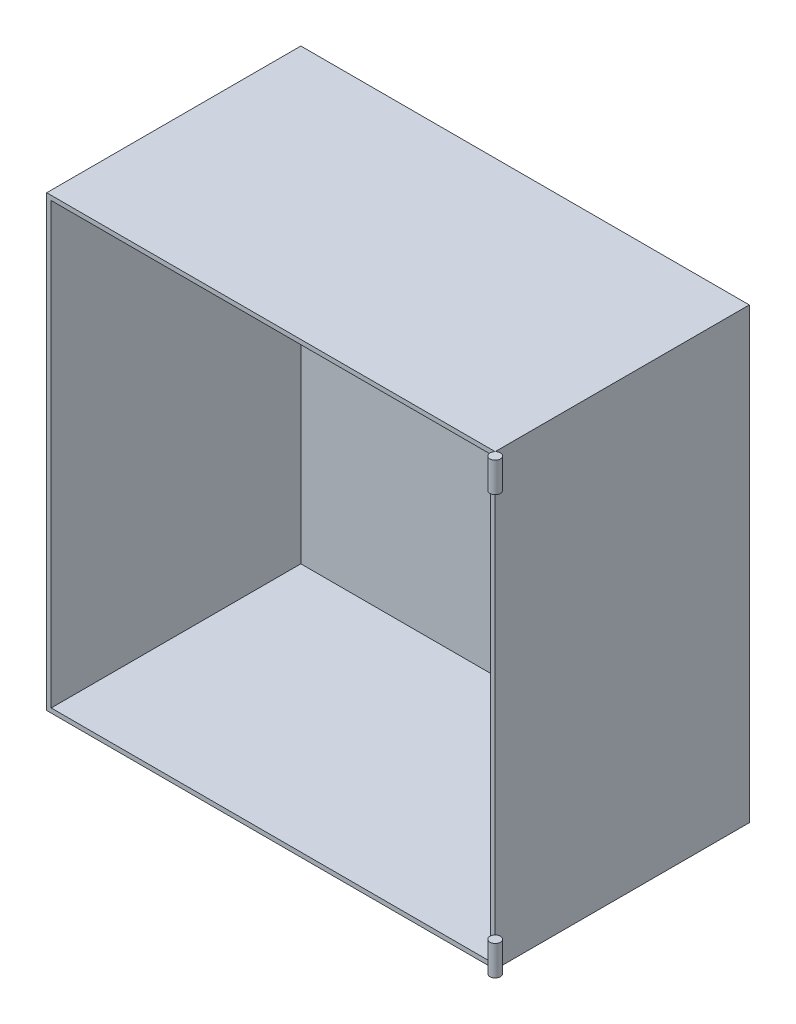
SolidWorks part; units mm, degrees
ref_plane "Alzado" through (0, 0, 0) normal (0, 0, 1) x (1, 0, 0)
ref_plane "Planta" through (0, 0, 0) normal (0, 1, 0) x (1, 0, 0)
ref_plane "Vista lateral" through (0, 0, 0) normal (1, 0, 0) x (0, 0, -1)
sketch "Croquis1" plane through (0, 0, 0) normal (0, 0, 1) x (1, 0, 0)
  line L1 (0, 0) -> (300, 0)
  line L2 (0, 0) -> (0, -300)
  line L3 (0, -300) -> (300, -300)
  line L4 (300, 0) -> (300, -300)
  dimension "D1" = 300
  dimension "D2" = 300
extrude "Saliente-Extruir1" add sketch "Croquis1" along normal blind 170
sketch "Croquis2" plane through (0, 0, 170) normal (0, 0, 1) x (1, 0, 0)
  line L16 (3, -297) -> (297, -297)
  line L17 (297, -297) -> (297, -3)
  line L18 (3, -3) -> (3, -297)
  line L19 (297, -3) -> (3, -3)
  line L20 (3, -297) -> (297, -297)
  line L21 (297, -297) -> (297, -3)
  line L22 (3, -3) -> (3, -297)
  line L23 (297, -3) -> (3, -3)
  dimension "D1" = 3
extrude "Cortar-Extruir1" cut sketch "Croquis2" against normal blind 167
sketch "Croquis3" plane through (0, 0, 0) normal (0, 1, 0) x (1, 0, 0)
  line L0 (300, -170) -> (302.4749, -172.4749) construction
  circle A0 centre (302.4749, -172.4749) radius 3.5
  dimension "D1" = 3.5
extrude "Saliente-Extruir2" add sketch "Croquis3" against normal blind 20 separate body
sketch "Croquis4" plane through (0, -300, 0) normal (0, -1, 0) x (1, 0, 0)
  circle A0 centre (302.4749, 172.4749) radius 3.5
extrude "Saliente-Extruir3" add sketch "Croquis4" against normal blind 20 separate body
